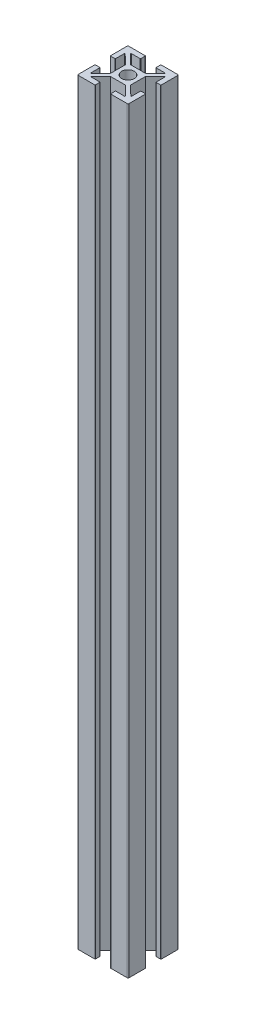
SolidWorks part; units mm, degrees
ref_plane "Front Plane" through (0, 0, 0) normal (0, 0, 1) x (1, 0, 0)
ref_plane "Top Plane" through (0, 0, 0) normal (0, 1, 0) x (1, 0, 0)
ref_plane "Right Plane" through (0, 0, 0) normal (1, 0, 0) x (0, 0, -1)
sketch "Sketch1" plane through (0, 0, 0) normal (0, 1, 0) x (1, 0, 0)
  line L0 (-9.8963, 3) -> (-8.1963, 3)
  line L3 (-3.1963, 10) -> (-9.6963, 10)
  line L4 (-10.0463, 3.15) -> (-10.0463, 9.65)
  line L7 (2.9332, 4) -> (-2.9332, 4)
  line L8 (-4, -2.9454) -> (-4, 2.9454)
  line L9 (-8.0463, 3.15) -> (-8.0463, 6.5862)
  line L10 (-6.6144, 8) -> (-3.1963, 8)
  line L11 (-3.0463, 8.15) -> (-3.0463, 9.85)
  line L12 (-8.0463, 8) -> (-4, 4) construction
  line L13 (-7.7908, 6.6929) -> (-4, 2.9454)
  line L14 (-6.7198, 7.7433) -> (-2.9332, 4)
  line L15 (8.0463, 8) -> (4, 4) construction
  line L22 (0, 0) -> (0, 11.6886) construction
  line L25 (0, 0) -> (-14.9841, 0) construction
  line L27 (6.7198, 7.7433) -> (2.9332, 4)
  line L28 (7.7908, 6.6929) -> (4, 2.9454)
  line L46 (3.0463, 8.15) -> (3.0463, 9.85)
  line L47 (6.6144, 8) -> (3.1963, 8)
  line L48 (8.0463, 3.15) -> (8.0463, 6.5862)
  line L49 (4, -2.9454) -> (4, 2.9454)
  line L50 (10.0463, 3.15) -> (10.0463, 9.65)
  line L51 (3.1963, 10) -> (9.6963, 10)
  line L52 (9.8963, 3) -> (8.1963, 3)
  line L53 (8.0463, -8) -> (4, -4) construction
  line L54 (-8.0463, -8) -> (-4, -4) construction
  line L55 (9.8963, -3) -> (8.1963, -3)
  line L56 (3.1963, -10) -> (9.6963, -10)
  line L57 (10.0463, -3.15) -> (10.0463, -9.65)
  line L58 (8.0463, -3.15) -> (8.0463, -6.5862)
  line L59 (6.6144, -8) -> (3.1963, -8)
  line L60 (3.0463, -8.15) -> (3.0463, -9.85)
  line L61 (7.7908, -6.6929) -> (4, -2.9454)
  line L62 (6.7198, -7.7433) -> (2.9332, -4)
  line L63 (-6.7198, -7.7433) -> (-2.9332, -4)
  line L64 (-7.7908, -6.6929) -> (-4, -2.9454)
  line L65 (-3.0463, -8.15) -> (-3.0463, -9.85)
  line L66 (-6.6144, -8) -> (-3.1963, -8)
  line L67 (-8.0463, -3.15) -> (-8.0463, -6.5862)
  line L68 (2.9332, -4) -> (-2.9332, -4)
  line L69 (-10.0463, -3.15) -> (-10.0463, -9.65)
  line L70 (-3.1963, -10) -> (-9.6963, -10)
  line L71 (-9.8963, -3) -> (-8.1963, -3)
  circle A0 centre (0, 0) radius 2.5
  arc A1 (-10.0463, 9.65) -> (-9.6963, 10) centre (-9.6963, 9.65) cw
  arc A2 (-9.8963, 3) -> (-10.0463, 3.15) centre (-9.8963, 3.15) cw
  arc A3 (-8.1963, 3) -> (-8.0463, 3.15) centre (-8.1963, 3.15) ccw
  arc A4 (-3.1963, 10) -> (-3.0463, 9.85) centre (-3.1963, 9.85) cw
  arc A5 (-3.1963, 8) -> (-3.0463, 8.15) centre (-3.1963, 8.15) ccw
  arc A6 (-6.7198, 7.7433) -> (-6.6144, 8) centre (-6.6144, 7.85) cw
  arc A7 (-7.7908, 6.6929) -> (-8.0463, 6.5862) centre (-7.8963, 6.5862) ccw
  arc A8 (7.7908, 6.6929) -> (8.0463, 6.5862) centre (7.8963, 6.5862) cw
  arc A9 (6.7198, 7.7433) -> (6.6144, 8) centre (6.6144, 7.85) ccw
  arc A10 (3.1963, 8) -> (3.0463, 8.15) centre (3.1963, 8.15) cw
  arc A11 (3.1963, 10) -> (3.0463, 9.85) centre (3.1963, 9.85) ccw
  arc A12 (8.1963, 3) -> (8.0463, 3.15) centre (8.1963, 3.15) cw
  arc A13 (9.8963, 3) -> (10.0463, 3.15) centre (9.8963, 3.15) ccw
  arc A14 (10.0463, 9.65) -> (9.6963, 10) centre (9.6963, 9.65) ccw
  arc A15 (10.0463, -9.65) -> (9.6963, -10) centre (9.6963, -9.65) cw
  arc A16 (9.8963, -3) -> (10.0463, -3.15) centre (9.8963, -3.15) cw
  arc A17 (8.1963, -3) -> (8.0463, -3.15) centre (8.1963, -3.15) ccw
  arc A18 (3.1963, -10) -> (3.0463, -9.85) centre (3.1963, -9.85) cw
  arc A19 (3.1963, -8) -> (3.0463, -8.15) centre (3.1963, -8.15) ccw
  arc A20 (6.7198, -7.7433) -> (6.6144, -8) centre (6.6144, -7.85) cw
  arc A21 (7.7908, -6.6929) -> (8.0463, -6.5862) centre (7.8963, -6.5862) ccw
  arc A22 (-7.7908, -6.6929) -> (-8.0463, -6.5862) centre (-7.8963, -6.5862) cw
  arc A23 (-6.7198, -7.7433) -> (-6.6144, -8) centre (-6.6144, -7.85) ccw
  arc A24 (-3.1963, -8) -> (-3.0463, -8.15) centre (-3.1963, -8.15) cw
  arc A25 (-3.1963, -10) -> (-3.0463, -9.85) centre (-3.1963, -9.85) ccw
  arc A26 (-8.1963, -3) -> (-8.0463, -3.15) centre (-8.1963, -3.15) cw
  arc A27 (-9.8963, -3) -> (-10.0463, -3.15) centre (-9.8963, -3.15) ccw
  arc A28 (-10.0463, -9.65) -> (-9.6963, -10) centre (-9.6963, -9.65) ccw
  point P8 (-10.0463, 10)
  point P27 (-10.0463, 3)
  point P30 (3.0463, 8)
  point P31 (10.0463, -10)
  point P50 (4, 0)
  point P55 (-8.0463, 3)
  point P58 (-3.0463, 10)
  point P61 (-3.0463, 8)
  point P63 (0, 4)
  point P65 (3.0463, 10)
  point P66 (8.0463, 3)
  point P67 (10.0463, 3)
  point P68 (10.0463, 10)
  point P118 (-4, 0)
  point P119 (10.0463, -3)
  point P120 (8.0463, -3)
  point P121 (3.0463, -10)
  point P122 (0, -4)
  point P123 (-3.0463, -8)
  point P124 (-3.0463, -10)
  point P125 (-8.0463, -3)
  point P126 (3.0463, -8)
  point P127 (-10.0463, -3)
  point P128 (-10.0463, -10)
  dimension "D2" = 0.35
  dimension "D3" = 0.15
  dimension "D4" = 0.15
  dimension "D5" = 0.15
  dimension "D12" = 0.15
  dimension "D13" = 0.15
  dimension "D14" = 0.15
  dimension "D6" = 2
  dimension "D7" = 7
  dimension "D8" = 7
  dimension "D9" = 2
  dimension "D10" = 0.75
  dimension "D11" = 0.75
extrude "Boss-Extrude2" add sketch "Sketch1" along normal blind 300
